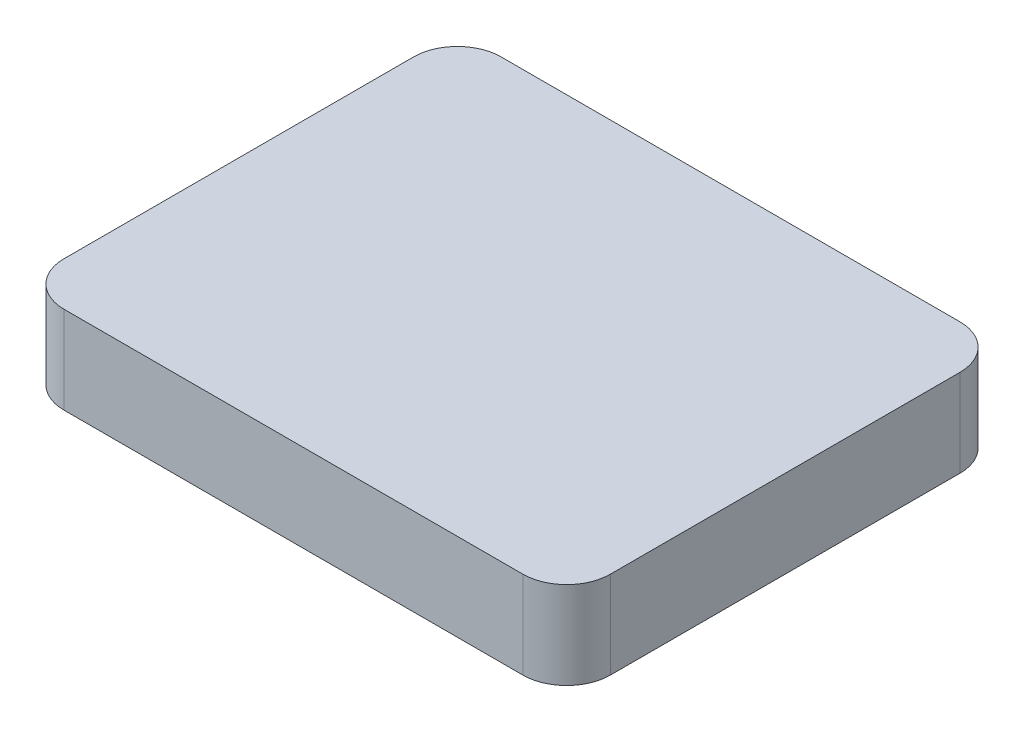
SolidWorks part; units mm, degrees
ref_plane "Front Plane" through (0, 0, 0) normal (0, 0, 1) x (1, 0, 0)
ref_plane "Top Plane" through (0, 0, 0) normal (0, 1, 0) x (1, 0, 0)
ref_plane "Right Plane" through (0, 0, 0) normal (1, 0, 0) x (0, 0, -1)
sketch "Sketch1" plane through (0, 0, 0) normal (0, 1, 0) x (1, 0, 0)
  line L1 (-57.7416, -115.9788) -> (152.2584, -115.9788)
  line L2 (-77.7416, -95.9788) -> (-77.7416, 64.0212)
  line L3 (-57.7416, 84.0212) -> (152.2584, 84.0212)
  line L4 (172.2584, -95.9788) -> (172.2584, 64.0212)
  arc A0 (-77.7416, 64.0212) -> (-57.7416, 84.0212) centre (-57.7416, 64.0212) cw
  arc A1 (152.2584, 84.0212) -> (172.2584, 64.0212) centre (152.2584, 64.0212) cw
  arc A2 (152.2584, -115.9788) -> (172.2584, -95.9788) centre (152.2584, -95.9788) ccw
  arc A3 (-57.7416, -115.9788) -> (-77.7416, -95.9788) centre (-57.7416, -95.9788) cw
  point P6 (-77.7416, 84.0212)
  point P9 (172.2584, 84.0212)
  point P14 (-77.7416, -115.9788)
  dimension "D3" = 20
  dimension "D4" = 20
  dimension "D1" = 250
  dimension "D2" = 200
extrude "Boss-Extrude1" add sketch "Sketch1" along normal blind 40
